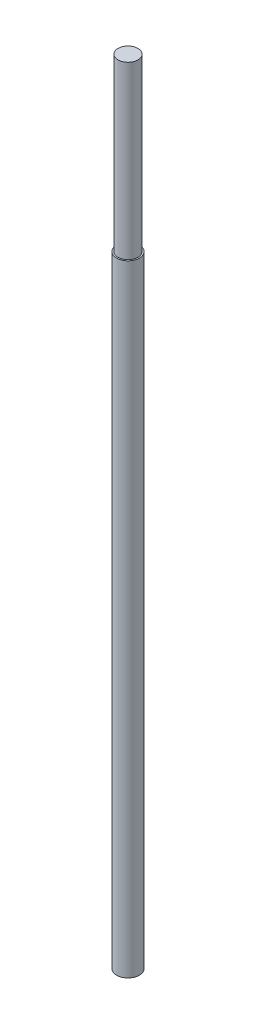
SolidWorks part; units mm, degrees
material "Chrome Stainless Steel"
ref_plane "Front Plane" through (0, 0, 0) normal (0, 0, 1) x (1, 0, 0)
ref_plane "Top Plane" through (0, 0, 0) normal (0, 1, 0) x (1, 0, 0)
ref_plane "Right Plane" through (0, 0, 0) normal (1, 0, 0) x (0, 0, -1)
sketch "Sketch1" plane through (0, 0, 0) normal (0, 1, 0) x (1, 0, 0)
  circle A0 centre (0, 0) radius 4
  dimension "D1" = 8
extrude "Boss-Extrude1" add sketch "Sketch1" along normal blind 218
sketch "Sketch2" plane through (0, 218, 0) normal (0, 1, 0) x (1, 0, 0)
  circle A0 centre (0, 0) radius 3.5
  circle A1 centre (0, 0) radius 4 construction
  dimension "D1" = 7
  dimension "D2" = 0
extrude "Boss-Extrude2" add sketch "Sketch2" along normal blind 60
